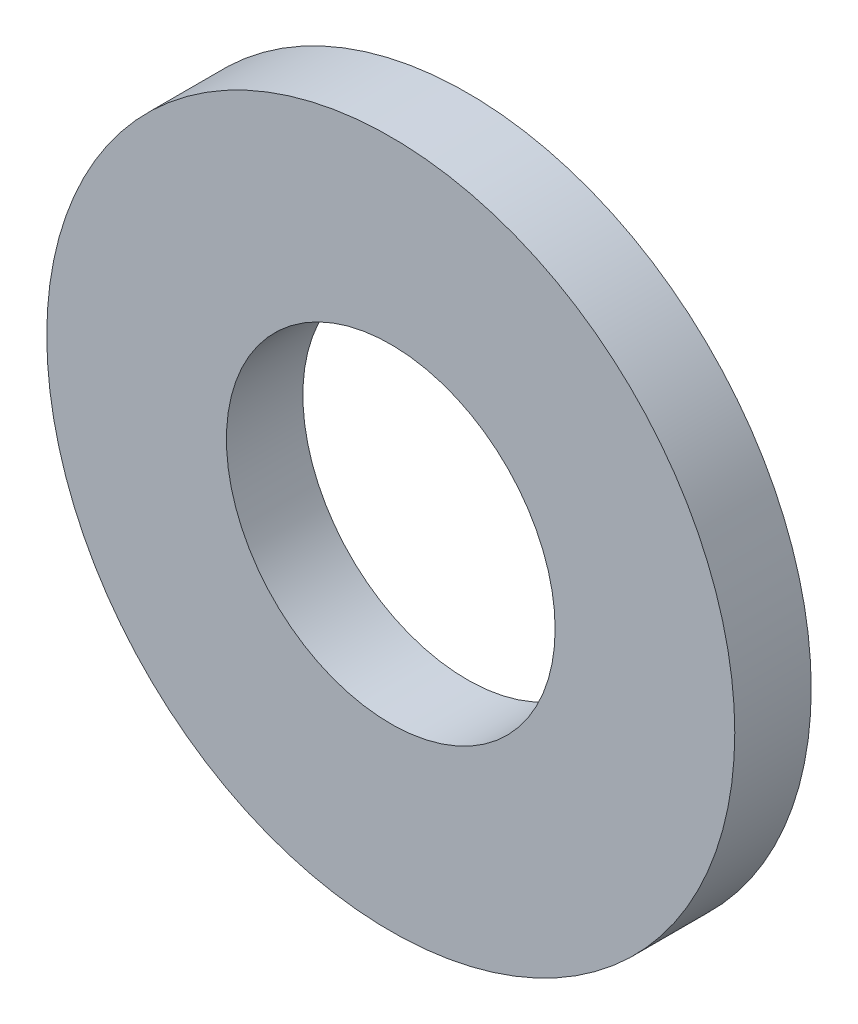
SolidWorks part; units mm, degrees
ref_plane "Front Plane" through (0, 0, 0) normal (0, 0, 1) x (1, 0, 0)
ref_plane "Top Plane" through (0, 0, 0) normal (0, 1, 0) x (1, 0, 0)
ref_plane "Right Plane" through (0, 0, 0) normal (1, 0, 0) x (0, 0, -1)
sketch "Sketch1" plane through (0, 0, 0) normal (0, 0, 1) x (1, 0, 0)
  circle A0 centre (0, 0) radius 2.15
  circle A1 centre (0, 0) radius 4.5
  dimension "D1" = 9
  dimension "D2" = 4.3
extrude "Boss-Extrude1" add sketch "Sketch1" along normal blind 1
